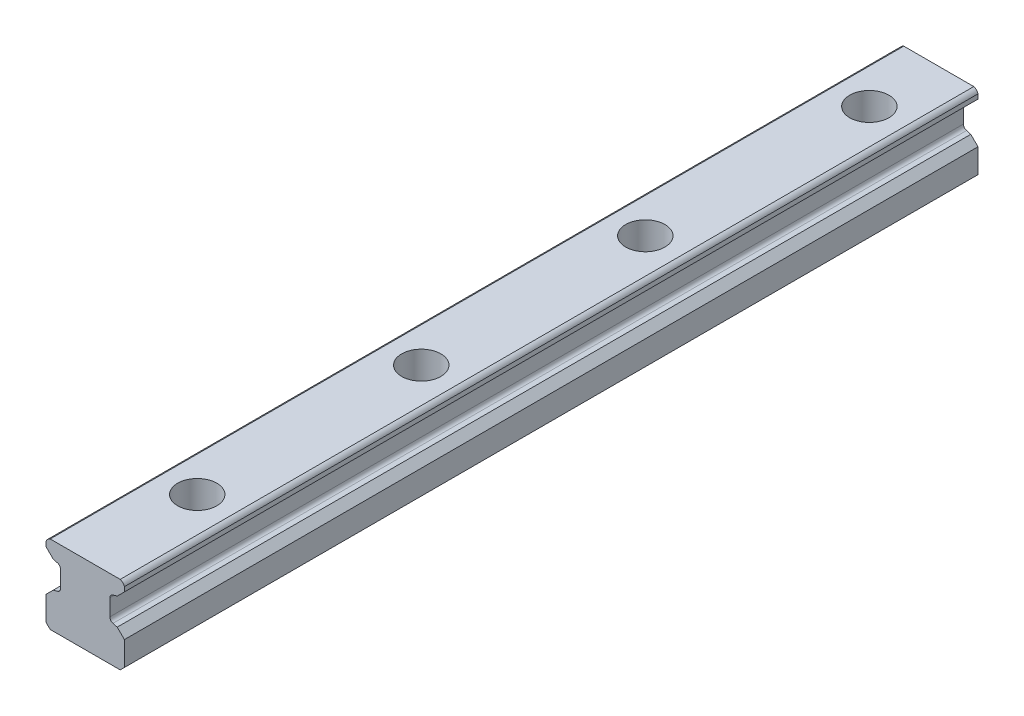
SolidWorks part; units mm, degrees
ref_plane "Front" through (0, 0, 0) normal (0, 0, 1) x (1, 0, 0)
ref_plane "Top" through (0, 0, 0) normal (0, 1, 0) x (1, 0, 0)
ref_plane "Right" through (0, 0, 0) normal (1, 0, 0) x (0, 0, -1)
sketch "Sketch1" plane through (0, 0, 0) normal (0, 0, 1) x (1, 0, 0)
  line L36 (-9.9118, 13.1068) -> (-11.43, 12.7)
  line L37 (-11.43, 12.7) -> (-14, 10.13)
  line L38 (-14, 10.13) -> (-14, 1.5)
  line L39 (-14, 1.5) -> (-12.5, 0)
  line L40 (-12.5, 0) -> (12.5, 0)
  line L41 (12.5, 0) -> (14, 1.5)
  line L42 (14, 1.5) -> (14, 10.13)
  line L43 (14, 10.13) -> (11.43, 12.7)
  line L44 (11.43, 12.7) -> (9.9118, 13.1068)
  line L45 (8.8, 14.5557) -> (8.8, 20.4443)
  line L46 (9.9118, 21.8932) -> (11.43, 22.3)
  line L47 (11.43, 22.3) -> (14, 24.87)
  line L48 (14, 24.87) -> (14, 26.5)
  line L49 (12.5, 28) -> (-12.5, 28)
  line L50 (-14, 26.5) -> (-14, 24.87)
  line L51 (-14, 24.87) -> (-11.43, 22.3)
  line L52 (-11.43, 22.3) -> (-9.9118, 21.8932)
  line L53 (-8.8, 20.4443) -> (-8.8, 14.5557)
  arc A12 (8.8, 14.5557) -> (9.9118, 13.1068) centre (10.3, 14.5557) ccw
  arc A13 (9.9118, 21.8932) -> (8.8, 20.4443) centre (10.3, 20.4443) ccw
  arc A14 (14, 26.5) -> (12.5, 28) centre (11.6492, 25.6492) ccw
  arc A15 (-12.5, 28) -> (-14, 26.5) centre (-11.6492, 25.6492) ccw
  arc A16 (-8.8, 20.4443) -> (-9.9118, 21.8932) centre (-10.3, 20.4443) ccw
  arc A17 (-9.9118, 13.1068) -> (-8.8, 14.5557) centre (-10.3, 14.5557) ccw
extrude "Boss-Extrude1" add sketch "Sketch1" along normal mid plane 1520
sketch "Sketch2" plane through (0, 0, 0) normal (1, 0, 0) x (0, 0, -1)
  line L0 (-720, 28) -> (-720, 0) construction
  line L3 (-720, 28) -> (-713, 28)
  line L4 (-713, 28) -> (-713, 16)
  line L5 (-713, 16) -> (-715.5, 16)
  line L6 (-715.5, 16) -> (-715.5, 0)
  line L7 (-715.5, 0) -> (-720, 0)
  line L8 (-720, 0) -> (-720, 28)
  line L9 (-760, 28) -> (760, 28) construction
  line L10 (-760, 28) -> (-760, 26.5) construction
  line L11 (-760, 0) -> (760, 0) construction
  dimension "D1" = 40
  dimension "D2" = 14
  dimension "D3" = 9
  dimension "D4" = 12
revolve "Cut-Revolve1" cut sketch "Sketch2" angle 360 about L0
pattern_linear "LPattern1" count 2 spacing 80 along (0, 0, -1) of "Cut-Revolve1"
mirror "Mirror1" about plane through (0, 0, 0) normal (0, 0, 1) of "LPattern1", "Cut-Revolve1"
pattern_linear "LPattern2" count 9 spacing 160 along (0, 0, -1) of "LPattern1", "Cut-Revolve1"
sketch "Sketch3" plane through (0, 0, 0) normal (1, 0, 0) x (0, 0, -1)
  line L0 (-713, 28) -> (-713, 16) construction
  line L1 (-713, 16) -> (-715.5, 16) construction
  line L2 (-715.5, 16) -> (-715.5, 0) construction
  line L3 (-720, 28) -> (-713, 28) construction
  line L4 (-715.5, 0) -> (-720, 0) construction
  line L5 (-713, 28) -> (-713, 16)
  line L6 (-713, 16) -> (-715.5, 16)
  line L7 (-715.5, 16) -> (-715.5, 0)
  line L8 (-727, 28) -> (-713, 28)
  line L9 (-715.5, 0) -> (-724.5, 0)
  line L10 (-720, 28) -> (-720, 0) construction
  line L11 (-724.5, 16) -> (-724.5, 0)
  line L12 (-727, 16) -> (-724.5, 16)
  line L13 (-727, 28) -> (-727, 16)
  line L14 (-633, 28) -> (-633, 16)
  line L15 (-633, 16) -> (-635.5, 16)
  line L16 (-635.5, 16) -> (-635.5, 0)
  line L17 (-647, 28) -> (-633, 28)
  line L18 (-635.5, 0) -> (-644.5, 0)
  line L19 (-640, 28) -> (-640, 0) construction
  line L20 (-644.5, 16) -> (-644.5, 0)
  line L21 (-647, 16) -> (-644.5, 16)
  line L22 (-647, 28) -> (-647, 16)
  line L23 (-644.5, 0) -> (-635.5, 0) construction
  line L24 (727, 28) -> (727, 16)
  line L25 (727, 16) -> (724.5, 16)
  line L26 (724.5, 16) -> (724.5, 0)
  line L27 (713, 28) -> (727, 28)
  line L28 (724.5, 0) -> (715.5, 0)
  line L29 (720, 28) -> (720, 0) construction
  line L30 (715.5, 16) -> (715.5, 0)
  line L31 (713, 16) -> (715.5, 16)
  line L32 (713, 28) -> (713, 16)
  line L33 (715.5, 0) -> (724.5, 0) construction
ref_plane "Plane1" [suppressed] through (0, 0, 200) normal (0, 0, 1) x (1, 0, 0)
sketch "Sketch4" [suppressed] plane through (0, 0, 200) normal (0, 0, 1) x (1, 0, 0)
  line L0 (-7, 28) -> (7, 28)
  line L1 (7, 28) -> (-7, 28) construction
  line L2 (12.5, 28) -> (-12.5, 28) construction
  line L3 (7, 28) -> (7, 16)
  line L4 (7, 16) -> (-7, 16) construction
  line L5 (7, 16) -> (4.5, 16)
  line L6 (4.5, 16) -> (-4.5, 16) construction
  line L7 (4.5, 16) -> (4.5, 0)
  line L8 (4.5, 0) -> (-4.5, 0)
  line L9 (-4.5, 0) -> (4.5, 0) construction
  line L10 (0, 0) -> (0, 28) construction
  line L11 (-4.5, 16) -> (-4.5, 0)
  line L12 (-7, 16) -> (-4.5, 16)
  line L13 (-7, 28) -> (-7, 16)
sketch "Sketch5" plane through (0, 0, 0) normal (0, 1, 0) x (1, 0, 0)
  line L0 (12.5, -760) -> (-12.5, -760) construction
  line L1 (-113.8413, 765.6499) -> (193.3339, 765.6499)
  line L2 (-113.8413, 765.6499) -> (-113.8413, -455.2)
  line L3 (-113.8413, -455.2) -> (193.3339, -455.2)
  line L4 (193.3339, 765.6499) -> (193.3339, -455.2)
  point P6 (0, -760)
  dimension "D1" = 304.8
extrude "Cut-Extrude1" cut sketch "Sketch5" against normal blind 20 and the other way blind 40
equation "\"D3@LPattern2\"=\"D3@LPattern1\"*2"
